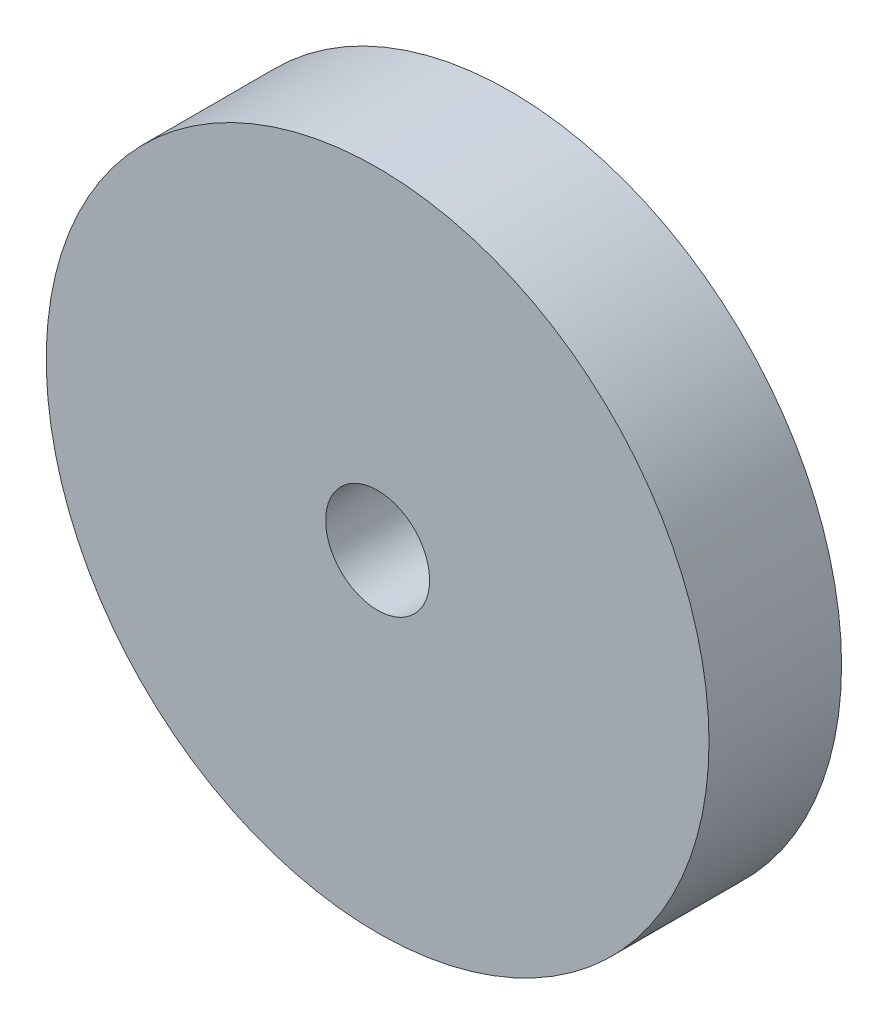
SolidWorks part; units mm, degrees
material "6061-T6 (SS)"
ref_plane "Front Plane" through (0, 0, 0) normal (0, 0, 1) x (1, 0, 0)
ref_plane "Top Plane" through (0, 0, 0) normal (0, 1, 0) x (1, 0, 0)
ref_plane "Right Plane" through (0, 0, 0) normal (1, 0, 0) x (0, 0, -1)
sketch "Sketch1" plane through (0, 0, 0) normal (0, 0, 1) x (1, 0, 0)
  circle A0 centre (0, 0) radius 15.875
  dimension "D1" = 31.75
extrude "Boss-Extrude1" add sketch "Sketch1" along normal blind 6.35
sketch "Sketch2" plane through (0, 0, 6.35) normal (0, 0, 1) x (1, 0, 0)
  circle A0 centre (0, 0) radius 2.4892
  point P2 (0, 0)
  dimension "D3" = 4.9784
extrude "Cut-Extrude1" cut sketch "Sketch2" against normal through all
